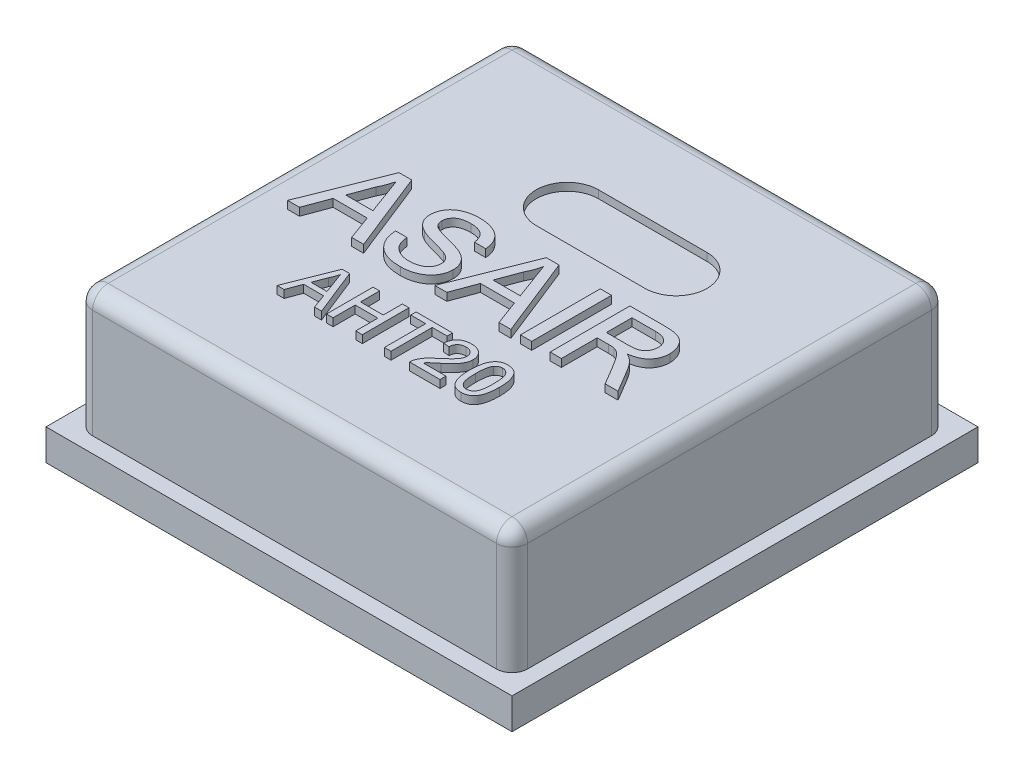
SolidWorks part; units mm, degrees
ref_plane "Спереди" through (0, 0, 0) normal (0, 0, 1) x (1, 0, 0)
ref_plane "Сверху" through (0, 0, 0) normal (0, 1, 0) x (1, 0, 0)
ref_plane "Справа" through (0, 0, 0) normal (1, 0, 0) x (0, 0, -1)
sketch "Эскиз1" plane through (0, 0, 0) normal (0, 1, 0) x (1, 0, 0)
  line L1 (-1.5, 1.5) -> (1.5, 1.5)
  line L2 (-1.5, 1.5) -> (-1.5, -1.5)
  line L3 (-1.5, -1.5) -> (1.5, -1.5)
  line L4 (1.5, 1.5) -> (1.5, -1.5)
  line L5 (-1.5, 1.5) -> (1.5, -1.5) construction
  line L6 (-1.5, -1.5) -> (1.5, 1.5) construction
  point P0 (0, 0)
  dimension "D1" = 3
  dimension "D2" = 3
extrude "Бобышка-Вытянуть1" add sketch "Эскиз1" along normal blind 0.2
sketch "Эскиз5" plane through (0, 0, 0) normal (0, -1, 0) x (1, 0, 0)
  line L0 (-0.725, -1.2) -> (-0.725, -0.8)
  line L1 (1.275, -1.2) -> (0.725, -1.2)
  line L2 (1.275, -1.2) -> (1.275, -0.8)
  line L3 (1.275, -0.8) -> (0.725, -0.8)
  line L4 (0.725, -1.2) -> (0.725, -0.8)
  line L5 (1.275, -1.2) -> (0.725, -0.8) construction
  line L6 (1.275, -0.8) -> (0.725, -1.2) construction
  line L7 (-0.725, -1.2) -> (-1.275, -1.2)
  line L8 (-1.275, -1.2) -> (-1.275, -0.8)
  line L9 (-0.725, -0.8) -> (-1.275, -0.8)
  line L10 (-0.725, -0.2) -> (-0.725, 0.2)
  line L11 (-0.725, -0.2) -> (-1.275, -0.2)
  line L12 (-1.275, -0.2) -> (-1.275, 0.2)
  line L13 (-0.725, 0.2) -> (-1.275, 0.2)
  line L14 (-0.725, 0.8) -> (-0.725, 1.2)
  line L15 (-0.725, 0.8) -> (-1.275, 0.8)
  line L16 (-1.275, 0.8) -> (-1.275, 1.2)
  line L17 (-0.725, 1.2) -> (-1.275, 1.2)
  line L18 (1.275, -0.2) -> (1.275, 0.2)
  line L19 (1.275, -0.2) -> (0.725, -0.2)
  line L20 (0.725, -0.2) -> (0.725, 0.2)
  line L21 (1.275, 0.2) -> (0.725, 0.2)
  line L22 (1.275, 0.8) -> (1.275, 1.2)
  line L23 (1.275, 0.8) -> (0.725, 0.8)
  line L24 (0.725, 0.8) -> (0.725, 1.2)
  line L25 (1.275, 1.2) -> (0.725, 1.2)
  point P0 (1, -1)
  dimension "D1" = 0.4
  dimension "D2" = 0.55
  dimension "D3" = 1
  dimension "D4" = 1
  dimension "D5" = 2
  dimension "D6" = 3
extrude "Бобышка-Вытянуть4" add sketch "Эскиз5" along normal blind 0.05
sketch "Эскиз6" plane through (0, 0.2, 0) normal (0, 1, 0) x (1, 0, 0)
  line L1 (-1.3, 1.4) -> (1.3, 1.4)
  line L2 (-1.4, 1.3) -> (-1.4, -1.3)
  line L3 (-1.3, -1.4) -> (1.3, -1.4)
  line L4 (1.4, 1.3) -> (1.4, -1.3)
  line L5 (-1.4, 1.4) -> (1.4, -1.4) construction
  line L6 (-1.4, -1.4) -> (1.4, 1.4) construction
  arc A0 (1.4, 1.3) -> (1.3, 1.4) centre (1.3, 1.3) ccw
  arc A1 (1.3, -1.4) -> (1.4, -1.3) centre (1.3, -1.3) ccw
  arc A2 (-1.3, -1.4) -> (-1.4, -1.3) centre (-1.3, -1.3) cw
  arc A3 (-1.4, 1.3) -> (-1.3, 1.4) centre (-1.3, 1.3) cw
  point P0 (0, 0)
  dimension "D3" = 0.1
  dimension "D1" = 2.8
  dimension "D2" = 2.8
extrude "Бобышка-Вытянуть5" add sketch "Эскиз6" along normal blind 0.8
fillet "Скругление2" radius 0.1 8 edges at (1.3707, 1, -1.3707) (1.3707, 1, 1.3707) (-1.3707, 1, 1.3707) (-1.3707, 1, -1.3707) (1.4, 1, 0) (0, 1, 1.4) (-1.4, 1, 0) (0, 1, -1.4)
sketch "Эскиз7" plane through (0, 1, 0) normal (0, 1, 0) x (1, 0, 0)
  line L0 (-0.244, 0.6) -> (0.456, 0.6) construction
  line L1 (-0.244, 0.8) -> (0.456, 0.8)
  line L2 (-0.244, 0.4) -> (0.456, 0.4)
  line L4 (1.3, -1.3) -> (1.3, 1.3) construction
  line L6 (1.3, 1.4) -> (-1.3, 1.4) construction
  arc A0 (-0.244, 0.8) -> (-0.244, 0.4) centre (-0.244, 0.6) ccw
  arc A1 (0.456, 0.4) -> (0.456, 0.8) centre (0.456, 0.6) ccw
  point P2 (0.106, 0.6)
  dimension "D1" = 0.4
  dimension "D2" = 0.7
  dimension "D3" = 0.8
  dimension "D4" = 0.844
extrude "Вырез-Вытянуть2" cut sketch "Эскиз7" against normal blind 0.05
sketch "Эскиз8" plane through (0, 1, 0) normal (0, 1, 0) x (1, 0, 0)
  text T0 "ASAIR" font "Arial" height in points 2
  text T1 "AHT20" font "Arial" height 0.3
  point P2 (0, 0)
  point P3 (-0.7799, -0.8299)
  point P4 (-0.6879, -0.8179)
  point P5 (-1.1239, -0.31)
extrude "Бобышка-Вытянуть6" add sketch "Эскиз8" along normal blind 0.05
